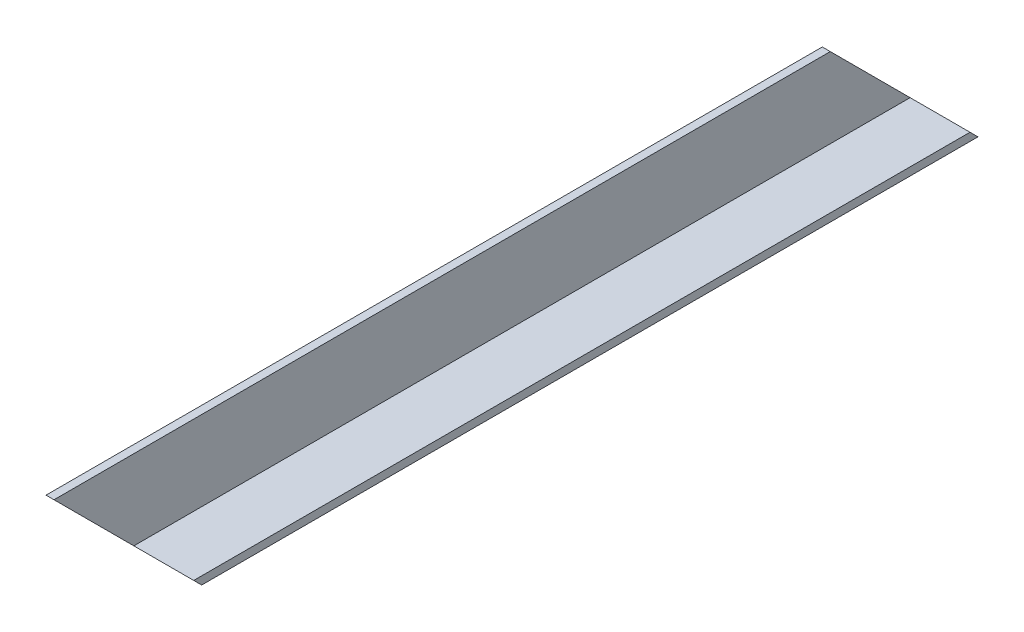
SolidWorks part; units mm, degrees
ref_plane "Front Plane" through (0, 0, 0) normal (0, 0, 1) x (1, 0, 0)
ref_plane "Top Plane" through (0, 0, 0) normal (0, 1, 0) x (1, 0, 0)
ref_plane "Right Plane" through (0, 0, 0) normal (1, 0, 0) x (0, 0, -1)
sketch "Sketch1" plane through (0, 0, 0) normal (0, 0, 1) x (1, 0, 0)
  line L0 (0, 0) -> (0, 22)
  line L1 (0, 22) -> (2, 22)
  line L2 (2, 22) -> (2, 2)
  line L3 (2, 2) -> (17, 2)
  line L4 (17, 2) -> (17, 0)
  line L5 (17, 0) -> (0, 0)
  dimension "D1" = 22
  dimension "D2" = 17
  dimension "D3" = 2
  dimension "D4" = 2
extrude "Boss-Extrude1" add sketch "Sketch1" along normal blind 250
sketch "Sketch2" plane through (17, 0, 0) normal (1, 0, 0) x (0, 0, -1)
  line L1 (-216.4544, 22) -> (-250, 22)
  line L5 (-250, 22) -> (-250, 0)
  line L8 (-22, 22) -> (0, 22)
  line L9 (-250, 22) -> (0, 22) construction
  line L10 (0, 22) -> (0, 0)
  line L11 (0, 0) -> (-22, 22)
  line L12 (-216.4544, 22) -> (-194.4544, 0)
  line L13 (-250, 0) -> (0, 0) construction
  line L14 (-250, 0) -> (-194.4544, 0)
  dimension "D1" = 45
  dimension "D2" = 137.5
extrude "Cut-Extrude1" cut sketch "Sketch2" against normal blind 150
